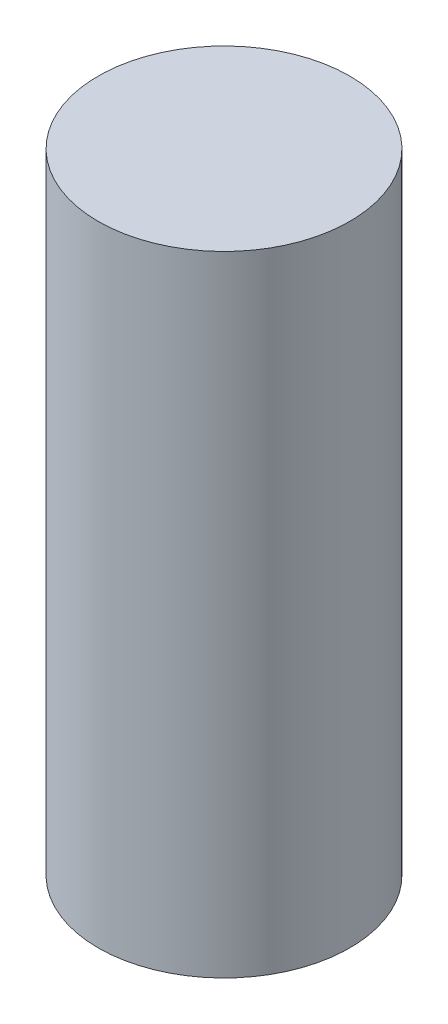
SolidWorks part; units mm, degrees
ref_plane "Płaszczyzna przednia" through (0, 0, 0) normal (0, 0, 1) x (1, 0, 0)
ref_plane "Płaszczyzna górna" through (0, 0, 0) normal (0, 1, 0) x (1, 0, 0)
ref_plane "Płaszczyzna prawa" through (0, 0, 0) normal (1, 0, 0) x (0, 0, -1)
sketch "Szkic1" plane through (0, 0, 0) normal (0, 1, 0) x (1, 0, 0)
  circle A0 centre (0, 0) radius 40
extrude "Dodanie-wyciągnięcie1" add sketch "Szkic1" along normal blind 200
